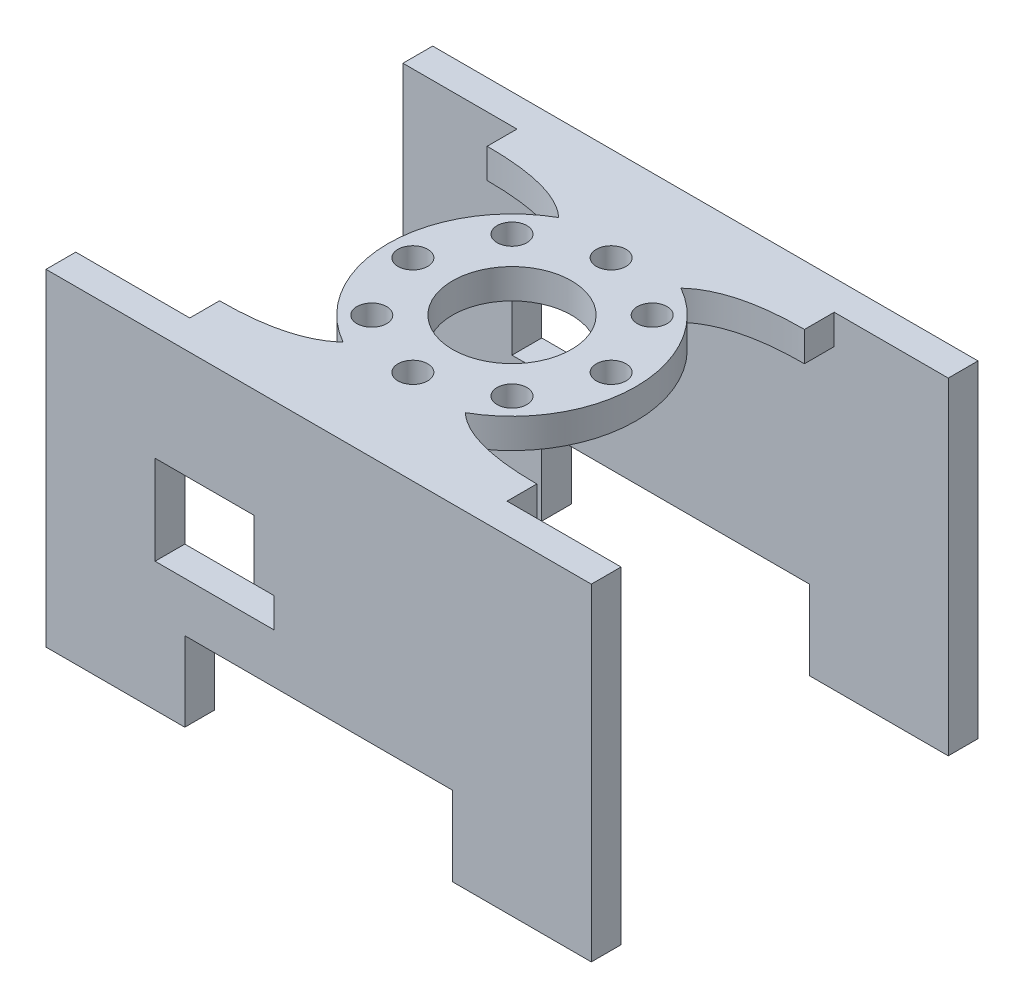
SolidWorks part; units mm, degrees
ref_plane "Plan de face" through (0, 0, 0) normal (0, 0, 1) x (1, 0, 0)
ref_plane "Plan de dessus" through (0, 0, 0) normal (0, 1, 0) x (1, 0, 0)
ref_plane "Plan de droite" through (0, 0, 0) normal (1, 0, 0) x (0, 0, -1)
sketch "Esquisse1" plane through (0, 0, 0) normal (0, 0, 1) x (1, 0, 0)
  line L0 (0, 0) -> (55, 0)
  line L1 (55, 0) -> (55, 33)
  line L2 (55, 33) -> (0, 33)
  line L3 (0, 33) -> (0, 0)
extrude "Boss.-Extru.1" add sketch "Esquisse1" along normal blind 3
sketch "Esquisse2" plane through (0, 0, 3) normal (0, 0, 1) x (1, 0, 0)
  line L0 (55, 0) -> (0, 0) construction
  line L1 (27.5, 0) -> (27.5, 8) construction
  line L2 (27.5, 8) -> (41, 8)
  line L3 (41, 8) -> (41, 0)
  line L4 (27.5, 8) -> (14, 8)
  line L5 (14, 8) -> (14, 0)
  line L6 (14, 0) -> (41, 0)
extrude "Enlèv. mat.-Extru.1" cut sketch "Esquisse2" against normal up to next
sketch "Esquisse3" plane through (0, 0, 3) normal (0, 0, 1) x (1, 0, 0)
  line L0 (0, 33) -> (11, 33) construction
  line L1 (55, 33) -> (0, 33) construction
  line L2 (11, 33) -> (11, 22) construction
  line L3 (11, 22) -> (21, 22)
  line L4 (21, 22) -> (21, 16)
  line L6 (11, 16) -> (11, 22)
  line L7 (11, 16) -> (11, 13)
  line L8 (11, 13) -> (23, 13)
  line L9 (23, 13) -> (23, 16)
  line L11 (21, 16) -> (23, 16)
  dimension "D1" = 11
  dimension "D2" = 11
  dimension "D3" = 6
  dimension "D4" = 3
  dimension "D5" = 12
extrude "Enlèv. mat.-Extru.2" cut sketch "Esquisse3" against normal up to next
sketch "Esquisse4" plane through (0, 33, 0) normal (0, 1, 0) x (1, 0, 0)
  line L0 (0, 0) -> (55, 0) construction
  line L1 (27.5, 0) -> (27.5, 33) construction
  line L2 (27.5, 0) -> (11.5, 0)
  line L3 (11.5, 0) -> (11.5, 3)
  line L4 (11.5, 3) -> (43.5, 3)
  line L5 (43.5, 3) -> (43.5, 0)
  line L6 (43.5, 0) -> (11.5, 0)
  line L7 (11.5, 3) -> (27.5, 3) construction
  line L8 (27.5, 3) -> (21.5, 16.5) construction
  line L9 (43.5, 3) -> (27.5, 3) construction
  line L10 (27.5, 3) -> (33.5, 16.5) construction
  line L11 (21.5, 16.5) -> (33.5, 16.5) construction
  line L12 (43.5, 33) -> (11.5, 33)
  line L13 (43.5, 30) -> (43.5, 33)
  line L14 (11.5, 30) -> (43.5, 30)
  line L15 (11.5, 33) -> (11.5, 30)
  line L16 (27.5, 33) -> (11.5, 33)
  line L17 (11.5, 30) -> (27.5, 30) construction
  line L18 (27.5, 30) -> (21.5, 16.5) construction
  line L19 (43.5, 30) -> (27.5, 30) construction
  line L20 (27.5, 30) -> (33.5, 16.5) construction
  circle A0 centre (27.5, 16.5) radius 12.5
  circle A1 centre (27.5, 16.5) radius 6
  spline S0 degree 2 poles (11.5, 3) (27.5, 3) (21.5, 16.5) knots 0 0 0 1 1 1
  spline S1 degree 2 poles (43.5, 3) (27.5, 3) (33.5, 16.5) knots 0 0 0 1 1 1
  spline S2 degree 2 poles (11.5, 30) (27.5, 30) (21.5, 16.5) knots 0 0 0 1 1 1
  spline S3 degree 2 poles (43.5, 30) (27.5, 30) (33.5, 16.5) knots 0 0 0 1 1 1
  line M6 (55, 0) -> (0, 0)
  dimension "D1" = 32
  dimension "D2" = 3
extrude "Boss.-Extru.2" add sketch "Esquisse4" against normal blind 3 contours L5 L4 L3 M6 | L4 S1 A0 S0 | A0 S1 A1 S0 | A0 S3 A1 S1 | S2 A0 S0 A1 | S3 A0 S2 A1 | S3 L14 S2 A0 | L12 L15 L14 L13
sketch "Esquisse5" plane through (0, 33, 0) normal (0, 1, 0) x (1, 0, 0)
  line L0 (27.5, 26.5) -> (27.5, 16.5) construction
  line L1 (27.5, 16.5) -> (27.5, 6.5) construction
  line L2 (27.5, 16.5) -> (37.5, 16.5) construction
  line L3 (27.5, 16.5) -> (17.5, 16.5) construction
  line L4 (27.5, 16.5) -> (20.4289, 23.5711) construction
  line L5 (27.5, 16.5) -> (34.5711, 9.4289) construction
  line L6 (27.5, 16.5) -> (20.4289, 9.4289) construction
  line L7 (27.5, 16.5) -> (34.5711, 23.5711) construction
  circle A0 centre (27.5, 16.5) radius 6 construction
  circle A1 centre (27.5, 16.5) radius 12.5 construction
  circle A2 centre (27.5, 16.5) radius 10 construction
  circle A3 centre (27.5, 26.5) radius 1.5
  circle A4 centre (20.4289, 23.5711) radius 1.5
  circle A5 centre (17.5, 16.5) radius 1.5
  circle A6 centre (27.5, 6.5) radius 1.5
  circle A7 centre (34.5711, 9.4289) radius 1.5
  circle A8 centre (37.5, 16.5) radius 1.5
  circle A9 centre (34.5711, 23.5711) radius 1.5
  circle A10 centre (20.4289, 9.4289) radius 1.5
extrude "Enlèv. mat.-Extru.3" cut sketch "Esquisse5" against normal up to next
pattern_linear "Répétition linéaire1" count 2 spacing 36 along (0, 0, -1) of "Boss.-Extru.1", "Enlèv. mat.-Extru.1", "Enlèv. mat.-Extru.2"
